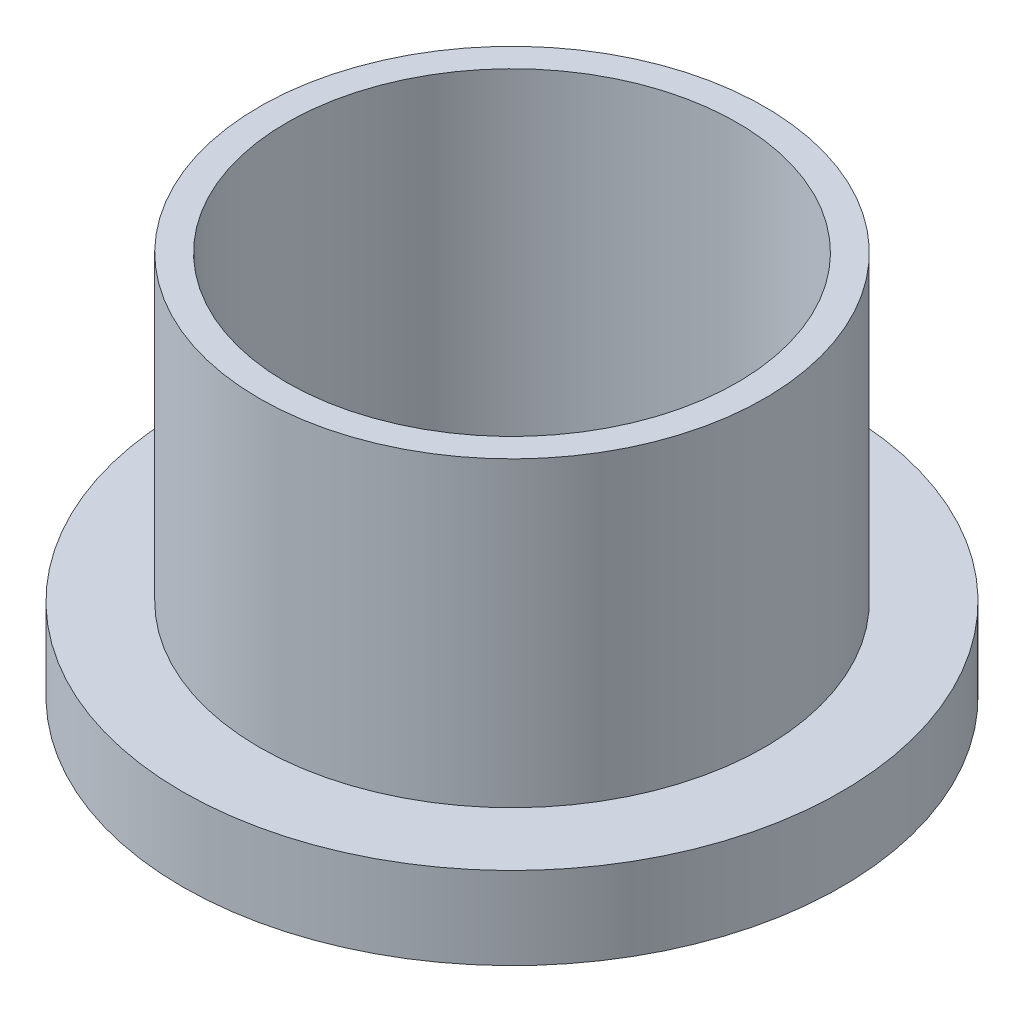
SolidWorks part; units mm, degrees
material "Alloy Steel"
ref_plane "Front Plane" through (0, 0, 0) normal (0, 0, 1) x (1, 0, 0)
ref_plane "Top Plane" through (0, 0, 0) normal (0, 1, 0) x (1, 0, 0)
ref_plane "Right Plane" through (0, 0, 0) normal (1, 0, 0) x (0, 0, -1)
sketch "BaseS" plane through (0, 0, 0) normal (0, 1, 0) x (1, 0, 0)
  circle A0 centre (0, 0) radius 4.1
  circle A1 centre (0, 0) radius 4.6
  dimension "InnerDia" = 8.2
  dimension "RefOuterDia" = 9.2
  dimension "Thickness" = 0.5
extrude "BASE" add sketch "BaseS" along normal blind 7
sketch "FlangeS" plane through (0, 0, 0) normal (0, 1, 0) x (1, 0, 0)
  circle A0 centre (0, 0) radius 6
  circle A1 centre (0, 0) radius 4.6 construction
  circle A2 centre (0, 0) radius 4.6
  dimension "RefDia" = 12
  dimension "DiaControl" = 1.4
extrude "FLANGE" add sketch "FlangeS" along normal blind 1.5
